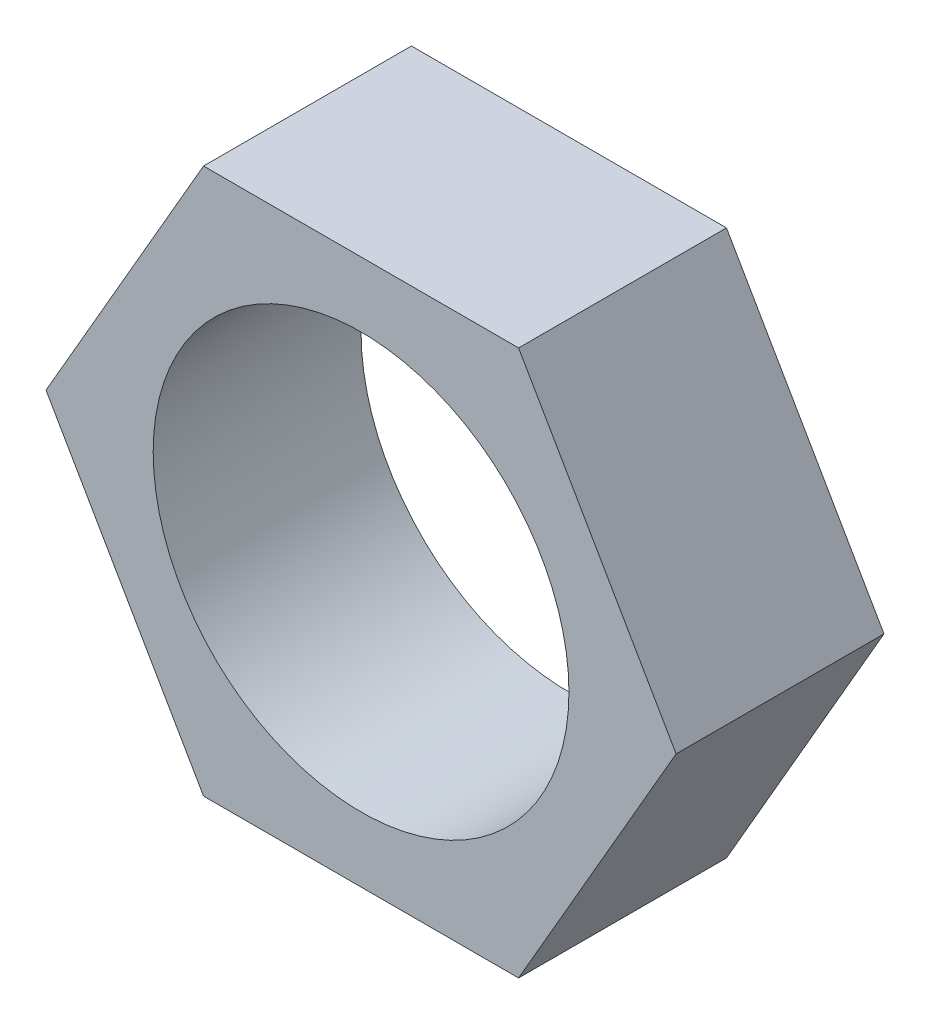
SolidWorks part; units mm, degrees
ref_plane "Front Plane" through (0, 0, 0) normal (0, 0, 1) x (1, 0, 0)
ref_plane "Top Plane" through (0, 0, 0) normal (0, 1, 0) x (1, 0, 0)
ref_plane "Right Plane" through (0, 0, 0) normal (1, 0, 0) x (0, 0, -1)
sketch "Sketch1" plane through (0, 0, 0) normal (0, 0, 1) x (1, 0, 0)
  line L1 (19.2474, 0) -> (9.6237, 16.6688)
  line L2 (9.6237, 16.6688) -> (-9.6237, 16.6688)
  line L3 (-9.6237, 16.6688) -> (-19.2474, 0)
  line L4 (-19.2474, 0) -> (-9.6237, -16.6688)
  line L5 (-9.6237, -16.6688) -> (9.6237, -16.6687)
  line L6 (9.6237, -16.6687) -> (19.2474, 0)
  circle A0 centre (0, 0) radius 16.6688 construction
  circle A1 centre (0, 0) radius 12.7
  dimension "D1" = 33.3375
  dimension "D2" = 16.6688
extrude "Boss-Extrude1" add sketch "Sketch1" along normal blind 12.7
